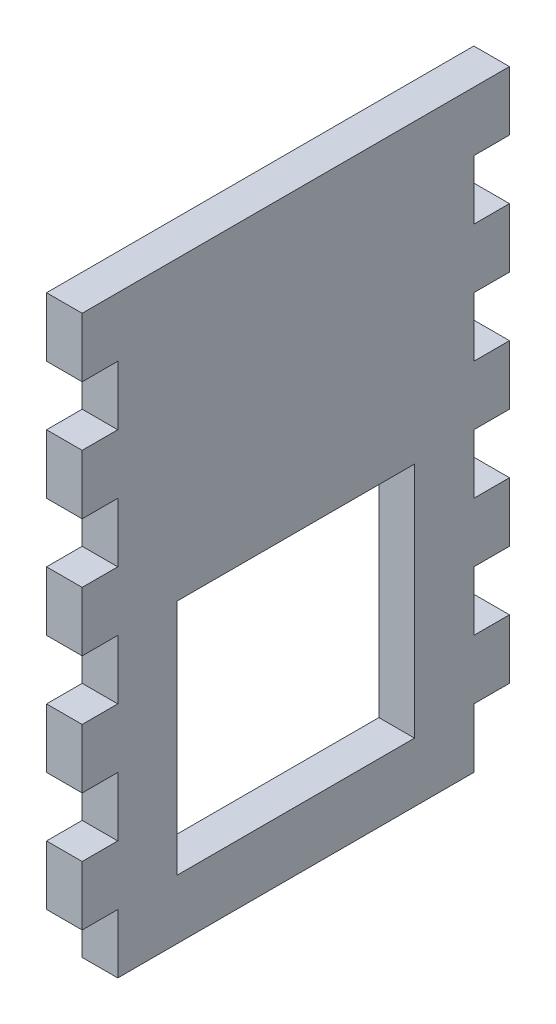
SolidWorks part; units mm, degrees
ref_plane "Plano frontal" through (0, 0, 0) normal (0, 0, 1) x (1, 0, 0)
ref_plane "Plano superior" through (0, 0, 0) normal (0, 1, 0) x (1, 0, 0)
ref_plane "Plano direito" through (0, 0, 0) normal (1, 0, 0) x (0, 0, -1)
sketch "Esboço1" plane through (0, 0, 0) normal (1, 0, 0) x (0, 0, -1)
  line L0 (-18.4969, 22.4792) -> (-18.4969, 17.4792)
  line L1 (-18.4969, 22.4792) -> (17.5031, 22.4792)
  line L5 (-10.4969, -2.5208) -> (9.5031, -2.5208)
  line L6 (-10.4969, -2.5208) -> (-10.4969, -22.5208)
  line L7 (-10.4969, -22.5208) -> (9.5031, -22.5208)
  line L8 (9.5031, -2.5208) -> (9.5031, -22.5208)
  line L9 (-18.4969, 17.4792) -> (-15.4969, 17.4792)
  line L10 (-15.4969, 17.4792) -> (-15.4969, 12.4792)
  line L11 (-15.4969, 12.4792) -> (-18.4969, 12.4792)
  line L12 (-15.4969, -27.5208) -> (14.5031, -27.5208)
  line L13 (-18.4969, 12.4792) -> (-18.4969, 7.4792)
  line L14 (-18.4969, 7.4792) -> (-15.4969, 7.4792)
  line L15 (-15.4969, 7.4792) -> (-15.4969, 2.4792)
  line L16 (-15.4969, 2.4792) -> (-18.4969, 2.4792)
  line L17 (-18.4969, 2.4792) -> (-18.4969, -2.5208)
  line L18 (-18.4969, -2.5208) -> (-15.4969, -2.5208)
  line L19 (-15.4969, -2.5208) -> (-15.4969, -7.5208)
  line L20 (-15.4969, -7.5208) -> (-18.4969, -7.5208)
  line L21 (-18.4969, -7.5208) -> (-18.4969, -12.5208)
  line L22 (-18.4969, -12.5208) -> (-15.4969, -12.5208)
  line L23 (-15.4969, -12.5208) -> (-15.4969, -17.5208)
  line L24 (-15.4969, -17.5208) -> (-18.4969, -17.5208)
  line L25 (-18.4969, -17.5208) -> (-18.4969, -22.5208)
  line L26 (-18.4969, -22.5208) -> (-15.4969, -22.5208)
  line L27 (-15.4969, -22.5208) -> (-15.4969, -27.5208)
  line L29 (17.5031, 12.4792) -> (17.5031, 7.4792)
  line L30 (14.5031, -22.5208) -> (14.5031, -27.5208)
  line L31 (17.5031, -22.5208) -> (14.5031, -22.5208)
  line L32 (17.5031, -17.5208) -> (17.5031, -22.5208)
  line L33 (14.5031, -17.5208) -> (17.5031, -17.5208)
  line L34 (14.5031, -12.5208) -> (14.5031, -17.5208)
  line L35 (17.5031, -12.5208) -> (14.5031, -12.5208)
  line L36 (17.5031, -7.5208) -> (17.5031, -12.5208)
  line L37 (14.5031, -7.5208) -> (17.5031, -7.5208)
  line L38 (14.5031, -2.5208) -> (14.5031, -7.5208)
  line L39 (17.5031, -2.5208) -> (14.5031, -2.5208)
  line L40 (17.5031, 2.4792) -> (17.5031, -2.5208)
  line L41 (14.5031, 2.4792) -> (17.5031, 2.4792)
  line L42 (14.5031, 7.4792) -> (14.5031, 2.4792)
  line L43 (17.5031, 7.4792) -> (14.5031, 7.4792)
  line L44 (14.5031, 12.4792) -> (17.5031, 12.4792)
  line L45 (14.5031, 17.4792) -> (14.5031, 12.4792)
  line L46 (17.5031, 17.4792) -> (14.5031, 17.4792)
  line L47 (17.5031, 22.4792) -> (17.5031, 17.4792)
  line L48 (-15.4969, -27.5208) -> (-18.4969, -27.5208) [skipped]
  point P1 (0, 0)
  point P2 (0, 0)
  point P8 (0, 0)
  point P13 (0, 0)
  point P54 (0, 0)
  point P55 (0, 0)
  dimension "D1" = 5
  dimension "D2" = 36
  dimension "D3" = 20
  dimension "D4" = 20
  dimension "D5" = 5
  dimension "D6" = 5
  dimension "D7" = 5
  dimension "D8" = 5
  dimension "D9" = 3
  dimension "D10" = 5
  dimension "D11" = 3
  dimension "D12" = 5
  dimension "D13" = 5
  dimension "D14" = 3
  dimension "D15" = 5
  dimension "D16" = 3
  dimension "D17" = 5
  dimension "D18" = 5
  dimension "D19" = 5
  dimension "D20" = 5
  dimension "D21" = 3
  dimension "D22" = 3
  dimension "D23" = 5
  dimension "D24" = 30
  dimension "D25" = 5
extrude "Ressalto-extrusão1" add sketch "Esboço1" along normal blind 3
